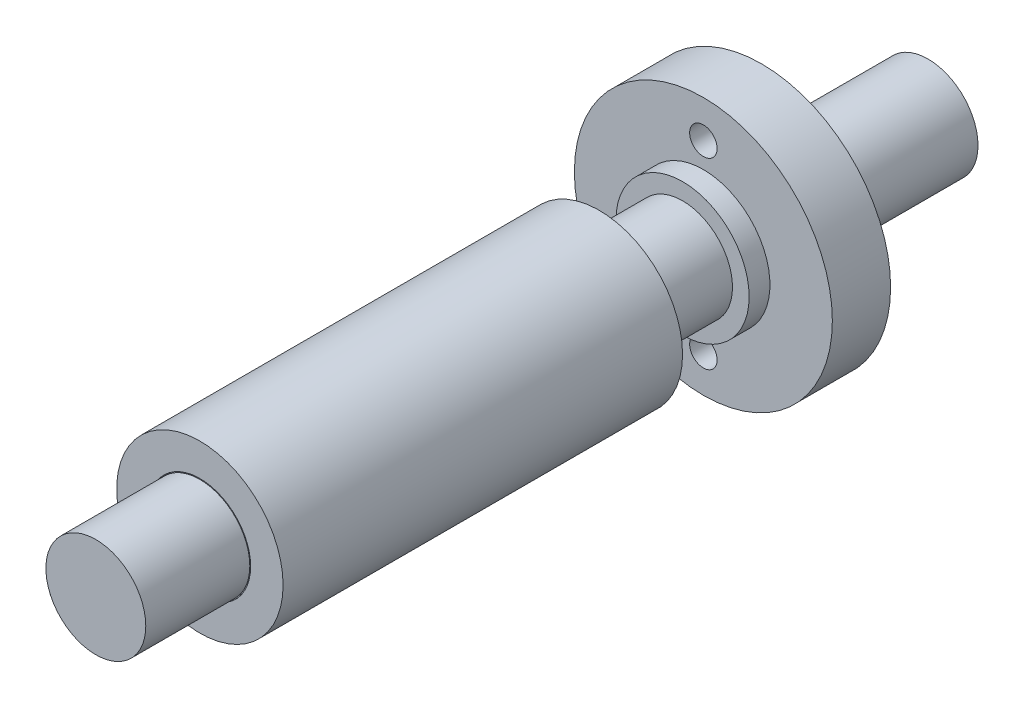
SolidWorks part; units mm, degrees
ref_plane "Front Plane" through (0, 0, 0) normal (0, 0, 1) x (1, 0, 0)
ref_plane "Top Plane" through (0, 0, 0) normal (0, 1, 0) x (1, 0, 0)
ref_plane "Right Plane" through (0, 0, 0) normal (1, 0, 0) x (0, 0, -1)
sketch "Sketch1" plane through (0, 0, 0) normal (0, 0, 1) x (1, 0, 0)
  circle A0 centre (0, 0) radius 6
  dimension "D1" = 12
extrude "Boss-Extrude1" add sketch "Sketch1" along normal blind 100
ref_plane "Plane1" through (0, 0, 20) normal (0, 0, -1) x (-1, 0, 0)
sketch "Sketch2" plane through (0, 0, 20) normal (0, 0, -1) x (-1, 0, 0)
  circle A0 centre (0, 0) radius 15.5
  dimension "D1" = 31
extrude "Boss-Extrude2" add sketch "Sketch2" against normal blind 7
sketch "Sketch3" plane through (0, 0, 27) normal (0, 0, 1) x (1, 0, 0)
  circle A0 centre (0, 0) radius 8
  dimension "D1" = 16
extrude "Boss-Extrude3" add sketch "Sketch3" along normal blind 2.5
ref_plane "Plane2" through (0, 0, 39.5) normal (0, 0, 1) x (1, 0, 0)
sketch "Sketch4" plane through (0, 0, 39.5) normal (0, 0, 1) x (1, 0, 0)
  circle A0 centre (0, 0) radius 10
  dimension "D1" = 20
extrude "Boss-Extrude4" add sketch "Sketch4" along normal blind 48
sketch "Sketch5" plane through (0, 0, 27) normal (0, 0, 1) x (1, 0, 0)
  circle A0 centre (0, 0) radius 11
  circle A1 centre (0, 11) radius 1.65
  circle A2 centre (0, -11) radius 1.65
  dimension "D1" = 22
  dimension "D2" = 3.3
extrude "Cut-Extrude1" cut sketch "Sketch5" against normal blind 48 contours A0 A1 | A0 A1 | A0 A2 | A0 A2
sketch "Sketch6" plane through (0, 0, 87.5) normal (0, 0, 1) x (1, 0, 0)
  circle A0 centre (0, 0) radius 6
  circle A1 centre (0, 0) radius 6.1
  dimension "D1" = 0.1
extrude "Cut-Extrude2" cut sketch "Sketch6" against normal up to surface (48 mm away) up to face at (6, 0, 39.5)
ref_plane "Plane3" through (0, 0, 39.5) normal (0, 0, 1) x (1, 0, 0)
sketch "Sketch7" plane through (0, 0, 39.5) normal (0, 0, 1) x (1, 0, 0)
  circle A0 centre (0, 0) radius 5.25
  circle A1 centre (0, 0) radius 6
  dimension "D1" = 10.5
extrude "Cut-Extrude3" cut sketch "Sketch7" along normal blind 1 contours A1 A0
ref_plane "Plane4" through (0, 0, 87.5) normal (0, 0, 1) x (1, 0, 0)
sketch "Sketch8" plane through (0, 0, 87.5) normal (0, 0, 1) x (1, 0, 0)
  circle A0 centre (0, 0) radius 6
  circle A1 centre (0, 0) radius 5.25
  dimension "D1" = 10.5
extrude "Cut-Extrude4" cut sketch "Sketch8" against normal blind 1
